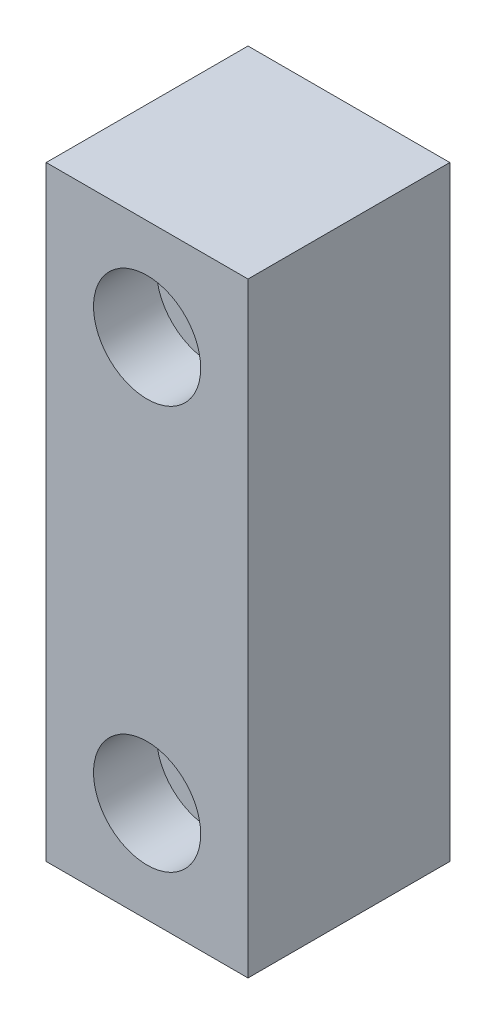
SolidWorks part; units mm, degrees
ref_plane "Front Plane" through (0, 0, 0) normal (1, 0, 0) x (0, 1, 0)
ref_plane "Top Plane" through (0, 0, 0) normal (0, 0, 1) x (0, 1, 0)
ref_plane "Right Plane" through (0, 0, 0) normal (0, 1, 0) x (-1, 0, 0)
sketch "Sketch1" plane through (0, 0, 0) normal (0, 0, 1) x (0, 1, 0)
  line L1 (-38.1, -12.7) -> (38.1, -12.7)
  line L2 (-38.1, -12.7) -> (-38.1, 12.7)
  line L3 (-38.1, 12.7) -> (38.1, 12.7)
  line L4 (38.1, -12.7) -> (38.1, 12.7)
  line L5 (-38.1, -12.7) -> (38.1, 12.7) construction
  line L6 (-38.1, 12.7) -> (38.1, -12.7) construction
  point P0 (0, 0)
  dimension "D1" = 38.1
  dimension "D2" = 12.7
extrude "Boss-Extrude1" add sketch "Sketch1" along normal mid plane 25.4
hole_wizard "CBORE for 5/16 Socket Head Cap Screw1" positions "Sketch3" profile "Sketch2" counterbore size "5/16" standard "ANSI Inch"
sketch "Sketch3" plane through (0, 0, 12.7) normal (0, 0, 1) x (1, 0, 0)
  line L0 (0, -25.4) -> (0, 25.4) construction
  line L1 (-12.7, 38.1) -> (-12.7, -38.1) construction
  line L2 (12.7, 38.1) -> (-12.7, 38.1) construction
  point P0 (0, -25.4)
  point P1 (0, 25.4)
  dimension "D1" = 12.7
  dimension "D2" = 12.7
  dimension "D3" = 63.5
sketch "Sketch2" plane through (0, -25.4, 12.7) normal (1, 0, 0) x (0, -1, 0)
  line L0 (0, 0) -> (0, 28.025)
  line L1 (0, 28.025) -> (4.3688, 25.4)
  line L2 (4.3688, 25.4) -> (4.3688, 7.9248)
  line L3 (4.3688, 7.9248) -> (6.7437, 7.9248)
  line L4 (6.7437, 7.9248) -> (6.7437, 0)
  line L5 (6.7437, 0) -> (0, 0)
  line L10 (0, 28.025) -> (-4.3688, 25.4) construction
  line L11 (0, -6.35) -> (0, 107.95) construction
  dimension "Hole Dia." = 8.7376
  dimension "Hole Depth" = 25.4
  dimension "C'Bore Dia." = 13.4874
  dimension "C'Bore Depth" = 7.9248
  dimension "Drill Angle" = 118
